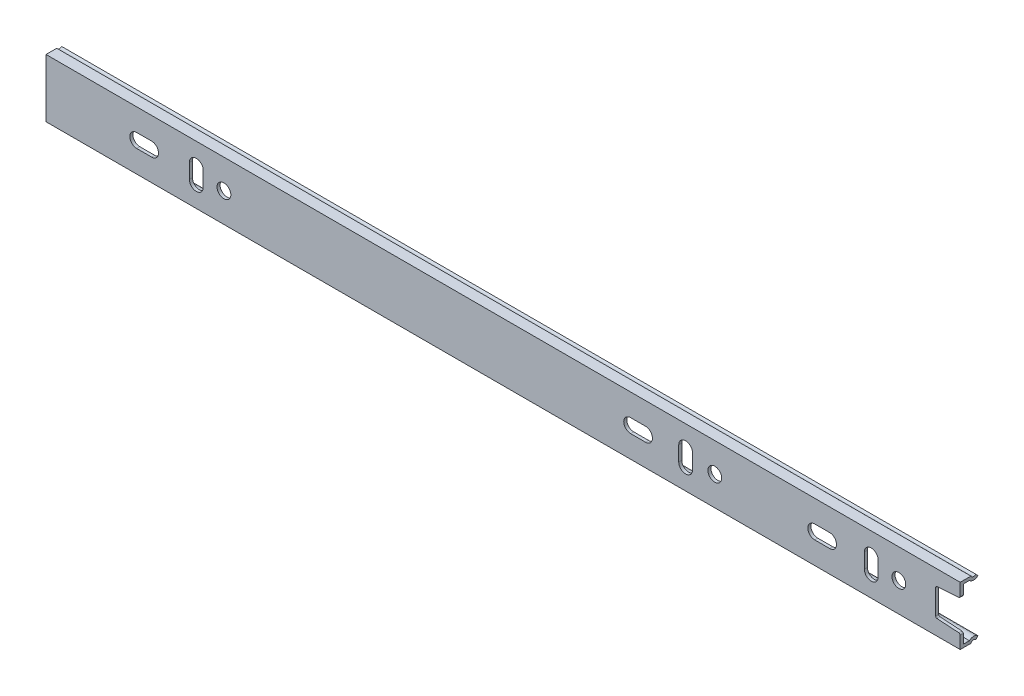
SolidWorks part; units mm, degrees
ref_plane "Front Plane" through (0, 0, 0) normal (0, 0, 1) x (1, 0, 0)
ref_plane "Top Plane" through (0, 0, 0) normal (0, 1, 0) x (1, 0, 0)
ref_plane "Right Plane" through (0, 0, 0) normal (1, 0, 0) x (0, 0, -1)
sketch "Sketch1" plane through (0, 0, 0) normal (1, 0, 0) x (0, 0, -1)
  line L0 (0, -22.85) -> (0, 22.85) construction
  line L1 (0, 22.85) -> (-12.7, 22.85) construction
  line L2 (-12.7, 22.85) -> (-12.7, 17.85) construction
  line L4 (0, -22.85) -> (-12.7, -22.85) construction
  line L5 (-12.7, -22.85) -> (-12.7, -17.85) construction
  line L6 (-12.7, 11.1778) -> (-10.7, 13.1778) construction
  line L7 (-10.7, 13.1778) -> (-8.35, 13.1778) construction
  line L8 (-1, 13.1778) -> (-1, 7) construction
  line L9 (-1, 7) -> (-4, 4) construction
  line L10 (-4, 4) -> (-4, -4) construction
  line L11 (-4, -4) -> (-1, -7) construction
  line L12 (-1, -7) -> (-1, -13.1778) construction
  line L13 (-1, -13.1778) -> (-3.35, -13.1778) construction
  line L14 (-10.7, -13.1778) -> (-12.7, -11.1778) construction
  line L15 (-3.35, 13.1778) -> (-1, 13.1778) construction
  line L16 (-6.2766, -22.85) -> (-6.2766, 16.5734) construction
  line L17 (-6.2766, 16.5734) -> (-6.5546, 16.5734) construction
  line L18 (-6.5546, 16.5734) -> (-6.5546, 16.5734) construction
  line L19 (0, 0) -> (-50000, 0) construction
  line L20 (-4, 0) -> (0, 0) construction
  line L21 (-8.35, -13.1778) -> (-10.7, -13.1778) construction
  line L22 (-11.9929, 10.4706) -> (-10.2858, 12.1778) construction
  line L23 (-10.2858, 12.1778) -> (-8.35, 12.1778) construction
  line L24 (-10.7543, 8.5) -> (-12.7543, 8.5)
  line L25 (-12.7543, 8.5) -> (-12.7543, -8.5)
  line L26 (-10.7543, 8.5) -> (-4.9126, 8.5) construction
  line L27 (-10.7543, -8.5) -> (-12.7543, -8.5)
  line L28 (-10.7543, -8.5) -> (-4.9126, -8.5) construction
  arc A1 (-8.35, 13.1778) -> (-3.35, 13.1778) centre (-5.85, 14.3234) ccw construction
  circle A2 centre (-5.85, 14.3234) radius 2.25 construction
  arc A3 (-8.35, -13.1778) -> (-3.35, -13.1778) centre (-5.85, -14.3234) cw construction
  circle A4 centre (-5.85, -14.3234) radius 2.25 construction
  circle A5 centre (-9.3538, 9.9278) radius 2.25 construction
  arc A6 (-10.7543, 8.5) -> (-7.9533, 8.5) centre (-9.3538, 9.9278) ccw
  arc A7 (-10.7543, -8.5) -> (-7.9533, -8.5) centre (-9.3538, -9.9278) cw
  circle A8 centre (-9.3538, -9.9278) radius 2.25 construction
  point P4 (0, 0)
  dimension "D3" = 4.5
  dimension "D4" = 0.5
  dimension "D8" = 2
  dimension "D1" = 45.7
  dimension "D2" = 12.7
  dimension "D5" = 2
  dimension "D6" = 5
  dimension "D7" = 1
  dimension "D9" = 3
  dimension "D10" = 5
  dimension "D11" = 14
  dimension "D14" = 2
  dimension "D15" = 17
  dimension "D12" = 1
extrude "Extrude-Thin1" add sketch "Sketch1" against normal blind 298 thin
sketch "Esboço1" plane through (0, 0, 13.7543) normal (0, 0, 1) x (1, 0, 0)
  line L0 (-268.425, 0) -> (-263.575, 0) construction
  line L1 (-268.425, 2.25) -> (-263.575, 2.25)
  line L2 (-268.425, -2.25) -> (-263.575, -2.25)
  line L3 (-249, 2.425) -> (-249, -2.425) construction
  line L4 (-246.75, 2.425) -> (-246.75, -2.425)
  line L5 (-251.25, 2.425) -> (-251.25, -2.425)
  line L6 (-8, 4.5) -> (-8, -4.5)
  line L7 (-47.425, 0) -> (-42.575, 0) construction
  line L8 (-47.425, 2.25) -> (-42.575, 2.25)
  line L9 (-47.425, -2.25) -> (-42.575, -2.25)
  line L10 (-29, 2.425) -> (-29, -2.425) construction
  line L11 (-26.75, 2.425) -> (-26.75, -2.425)
  line L12 (-31.25, 2.425) -> (-31.25, -2.425)
  line L13 (0, 5) -> (0, -5)
  line L14 (-107.425, 0) -> (-102.575, 0) construction
  line L15 (-107.425, 2.25) -> (-102.575, 2.25)
  line L16 (-107.425, -2.25) -> (-102.575, -2.25)
  line L17 (-89.5, 2.425) -> (-89.5, -2.425) construction
  line L18 (-87.25, 2.425) -> (-87.25, -2.425)
  line L19 (-91.75, 2.425) -> (-91.75, -2.425)
  line L20 (-298, 9.5) -> (-298, -9.5) construction
  line L21 (0, 9.5) -> (0, -9.5) construction
  line L22 (-8, 4.5) -> (0, 5)
  line L23 (-8, -4.5) -> (0, -5)
  arc A0 (-268.425, 2.25) -> (-268.425, -2.25) centre (-268.425, 0) ccw
  arc A1 (-263.575, -2.25) -> (-263.575, 2.25) centre (-263.575, 0) ccw
  arc A2 (-246.75, 2.425) -> (-251.25, 2.425) centre (-249, 2.425) ccw
  arc A3 (-251.25, -2.425) -> (-246.75, -2.425) centre (-249, -2.425) ccw
  circle A4 centre (-240, 0) radius 2.25
  arc A5 (-47.425, 2.25) -> (-47.425, -2.25) centre (-47.425, 0) ccw
  arc A6 (-42.575, -2.25) -> (-42.575, 2.25) centre (-42.575, 0) ccw
  arc A7 (-26.75, 2.425) -> (-31.25, 2.425) centre (-29, 2.425) ccw
  arc A8 (-31.25, -2.425) -> (-26.75, -2.425) centre (-29, -2.425) ccw
  circle A9 centre (-20, 0) radius 2.25
  arc A10 (-107.425, 2.25) -> (-107.425, -2.25) centre (-107.425, 0) ccw
  arc A11 (-102.575, -2.25) -> (-102.575, 2.25) centre (-102.575, 0) ccw
  arc A12 (-87.25, 2.425) -> (-91.75, 2.425) centre (-89.5, 2.425) ccw
  arc A13 (-91.75, -2.425) -> (-87.25, -2.425) centre (-89.5, -2.425) ccw
  circle A14 centre (-80, 0) radius 2.25
  point P3 (-266, 0)
  point P8 (-261.325, 0)
  point P9 (-270.675, 0)
  point P12 (-249, 0)
  point P17 (-249, 4.675)
  point P18 (-249, -4.675)
  point P26 (-45, 0)
  point P32 (0, 0)
  point P35 (-29, 0)
  point P44 (-8, 0)
  point P52 (-105, 0)
  point P61 (-89.5, 0)
  dimension "D1" = 9.35
  dimension "D7" = 4.5
  dimension "D2" = 4.5
  dimension "D3" = 4.5
  dimension "D4" = 9.35
  dimension "D5" = 32
  dimension "D6" = 49
  dimension "D8" = 58
  dimension "D9" = 193
  dimension "D10" = 208.5
  dimension "D11" = 218
  dimension "D12" = 45
  dimension "D13" = 29
  dimension "D14" = 20
  dimension "D15" = 9
  dimension "D16" = 10
  dimension "D17" = 8
extrude "Corte-extrusão1" cut sketch "Esboço1" against normal through all
fillet "Filete1" radius 0.5 4 edges at (-8, 4.5, 13.2543) (-8, -4.5, 13.2543) (0, -5, 13.2543) (0, 5, 13.2543)
